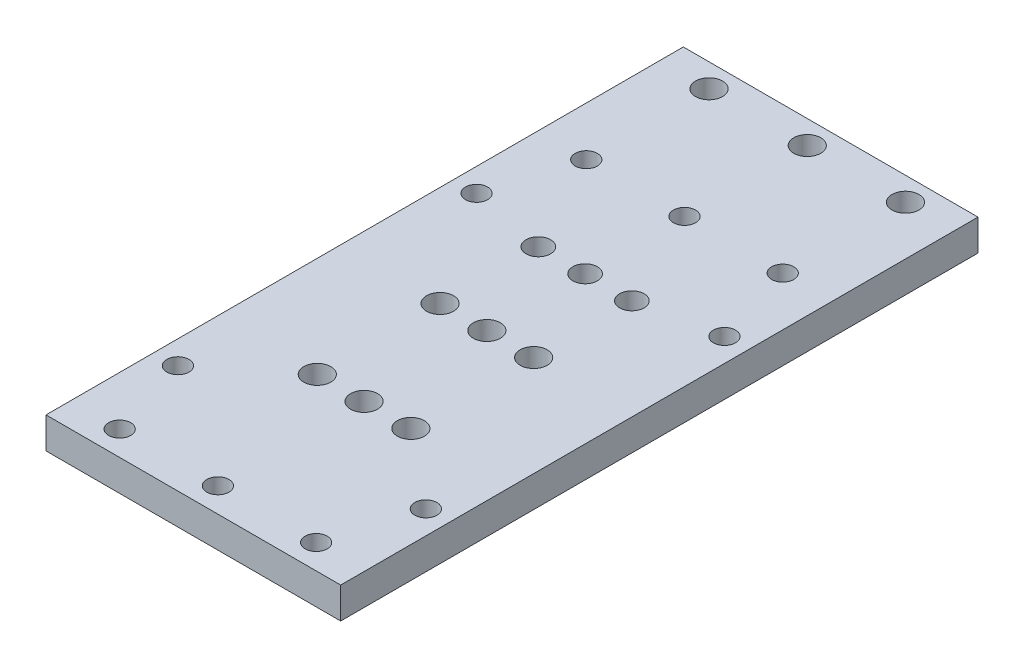
SolidWorks part; units mm, degrees
material "6061 Alloy"
ref_plane "Front Plane" through (0, 0, 0) normal (0, 0, 1) x (1, 0, 0)
ref_plane "Top Plane" through (0, 0, 0) normal (0, 1, 0) x (1, 0, 0)
ref_plane "Right Plane" through (0, 0, 0) normal (1, 0, 0) x (0, 0, -1)
sketch "Sketch1" plane through (0, 0, 0) normal (0, 1, 0) x (1, 0, 0)
  line L1 (-30, 80) -> (30, 80)
  line L2 (-30, 80) -> (-30, -80)
  line L3 (-30, -80) -> (30, -80)
  line L4 (30, 80) -> (30, -80)
  line L5 (0, -80) -> (0, 80) construction
  line L6 (-30, 0) -> (30, 0) construction
  point P0 (0, 0)
  dimension "D1" = 60
  dimension "D2" = 160
extrude "Boss-Extrude1" add sketch "Sketch1" along normal mid plane 6.35
sketch "Sketch3" plane through (0, 0, 0) normal (0, 1, 0) x (1, 0, 0)
  line L0 (0, 75.2375) -> (20, 75.2375) construction
  line L5 (0, -80) -> (0, 80) construction
  line L6 (-30, 0) -> (30, 0) construction
  line L7 (0, 50.2375) -> (20, 50.2375) construction
  line L8 (30, 80) -> (-30, 80) construction
  line L9 (-30, 80) -> (-30, -80) construction
  line L10 (-30, -80) -> (30, -80) construction
  line L11 (30, -80) -> (30, 80) construction
  line L12 (0, -44.7625) -> (20, -44.7625) construction
  circle A0 centre (20, 75.2375) radius 2.75
  circle A1 centre (20, 50.2375) radius 2.25
  circle A2 centre (-20, 50.2375) radius 2.25
  circle A3 centre (-20, 75.2375) radius 2.75
  circle A4 centre (0, 75.2375) radius 2.75
  circle A5 centre (0, 50.2375) radius 2.25
  circle A6 centre (20, -44.7625) radius 2.25
  circle A7 centre (-20, -44.7625) radius 2.25
  circle A8 centre (0, -44.7625) radius 2.25
  point P0 (0, 0)
  dimension "D4" = 5.5
  dimension "D5" = 4.5
  dimension "D1" = 4.7625
  dimension "D2" = 25
  dimension "D3" = 20
  dimension "D6" = 2
extrude "M4/5_through" cut sketch "Sketch3" against normal up to surface (3.175 mm away) and the other way blind 6.35 up to face at (0, -3.175, 0)
sketch "Sketch4" plane through (0, 0, -80) normal (0, 0, -1) x (-1, 0, 0)
  line L0 (0, 0) -> (-12, 0) construction
  line L1 (0, 0) -> (0, 3.175) construction
  line L2 (-30, 3.175) -> (30, 3.175) construction
  circle A0 centre (-12, 0) radius 1.5
  circle A1 centre (12, 0) radius 1.5
  dimension "D1" = 3
  dimension "D2" = 12
extrude "M3_DRILL" cut sketch "Sketch4" against normal blind 8
sketch "Sketch5" plane through (0, 3.175, 0) normal (0, 1, 0) x (1, 0, 0)
  line L0 (-20, -44.7625) -> (0, -44.7625) construction
  line L1 (-30, 80) -> (-30, -80) construction
  line L2 (0, 0) -> (0, -23.6676) construction
  line L3 (-20, 50.2375) -> (-20, -44.7625) construction
  line L4 (-20, 2.7375) -> (-9.1233, 2.7375) construction
  circle A0 centre (-25.2375, -27.6625) radius 2.25
  circle A1 centre (25.2375, -27.6625) radius 2.25
  circle A2 centre (25.2375, 33.1375) radius 2.25
  circle A3 centre (-25.2375, 33.1375) radius 2.25
  dimension "D2" = 4.5
  dimension "D1" = 17.1
  dimension "D3" = 4.7625
extrude "M4_through" cut sketch "Sketch5" against normal up to surface (6.35 mm away) up to face at (20, -3.175, -47.9875)
sketch "Sketch6" plane through (0, 3.175, 0) normal (0, 1, 0) x (1, 0, 0)
  line L0 (0, 0) -> (0, -64.4319) construction
  circle A0 centre (0, 30) radius 2.5
  circle A1 centre (9.53, 30) radius 2.5
  circle A2 centre (-9.53, 30) radius 2.5
  dimension "D1" = 5
  dimension "D4" = 30
  dimension "D2" = 2
  dimension "D3" = 2
extrude "M5_DRILL" cut sketch "Sketch6" against normal up to surface (6.35 mm away) up to face at (-25.2375, -3.175, -30.8875)
sketch "Sketch7" plane through (0, 3.175, 0) normal (0, 1, 0) x (1, 0, 0)
  line L0 (0, 30) -> (0, -15) construction
  circle A0 centre (0, 10) radius 2.75
  circle A1 centre (0, -15) radius 2.75
  circle A2 centre (9.53, 10) radius 2.75
  circle A3 centre (9.53, -15) radius 2.75
  circle A4 centre (-9.53, 10) radius 2.75
  circle A5 centre (-9.53, -15) radius 2.75
  dimension "D3" = 5.5
  dimension "D1" = 45
  dimension "D2" = 20
  dimension "D4" = 2
  dimension "D5" = 2
extrude "M5_through" cut sketch "Sketch7" against normal up to surface (6.35 mm away) up to face at (-9.53, -3.175, -27.5)
sketch "Sketch8" plane through (0, 3.175, 0) normal (0, 1, 0) x (1, 0, 0)
  line L0 (-20, -44.7625) -> (20, -44.7625) construction
  line L1 (30, -80) -> (30, 80) construction
  line L2 (-30, -80) -> (30, -80)
  line L3 (-30, -80) -> (-30, -49.7625)
  line L4 (-30, -49.7625) -> (30, -49.7625)
  line L5 (30, -80) -> (30, -49.7625)
  line L6 (0, -49.7625) -> (0, -80) construction
  line L7 (-30, -64.8812) -> (30, -64.8812) construction
  point P260 (0, -64.8812)
  dimension "D1" = 5
extrude "Cut-Extrude3" cut sketch "Sketch8" against normal up to surface (6.35 mm away) up to face at (-9.53, -3.175, -7.25)
